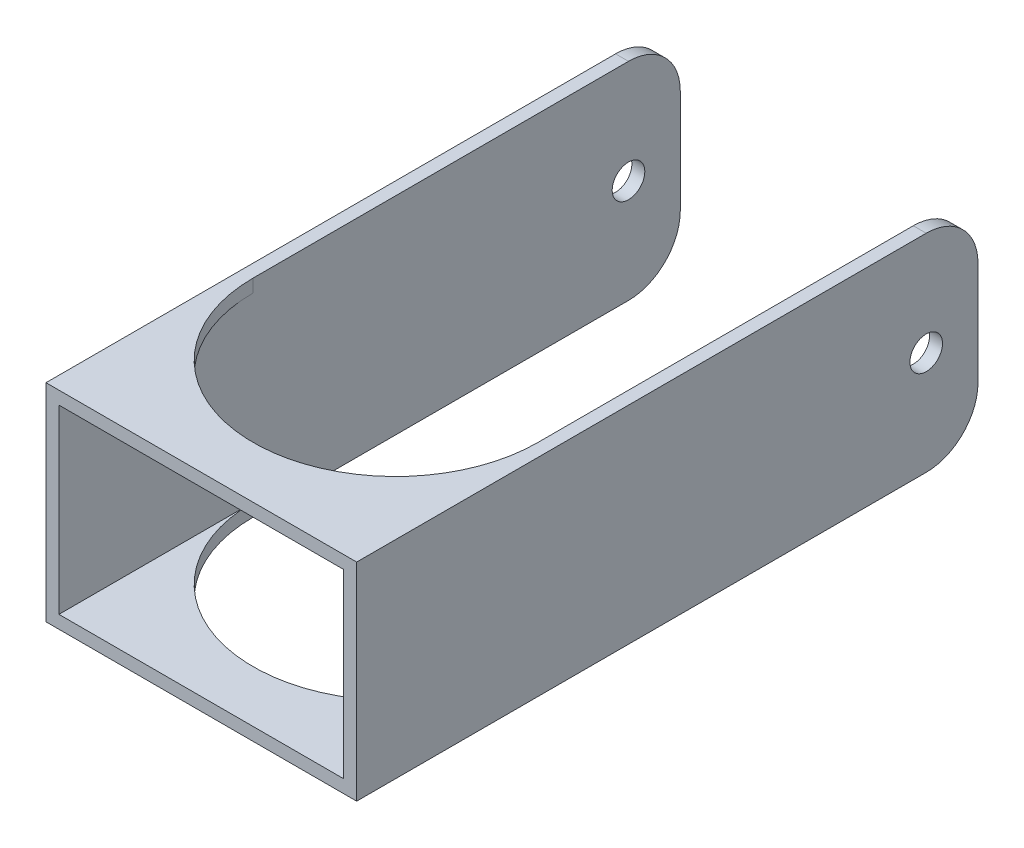
SolidWorks part; units mm, degrees
ref_plane "Front Plane" through (0, 0, 0) normal (0, 0, 1) x (1, 0, 0)
ref_plane "Top Plane" through (0, 0, 0) normal (0, 1, 0) x (1, 0, 0)
ref_plane "Right Plane" through (0, 0, 0) normal (1, 0, 0) x (0, 0, -1)
sketch "Sketch1" plane through (0, 0, 0) normal (0, 0, 1) x (1, 0, 0)
  line L0 (38.1, 0) -> (34.925, 0) construction
  line L1 (-38.1, 0) -> (38.1, 0) construction
  line L2 (0, 25.4) -> (0, -25.4)
  point P7 (0, 0)
sketch "Sketch2" plane through (0, 0, 0) normal (1, 0, 0) x (0, 0, -1)
  line L0 (76.2, 0) -> (-76.2, 0)
  point P4 (0, 0)
  dimension "Length" = 152.4
sketch "Sketch3" plane through (0, 0, 0) normal (0, 0, 1) x (1, 0, 0)
  line L0 (-38.1, 0) -> (38.1, 0) construction
  line L5 (38.1, -25.4) -> (-38.1, -25.4)
  line L6 (38.1, -25.4) -> (38.1, 25.4)
  line L11 (38.1, 25.4) -> (-38.1, 25.4)
  line L12 (-38.1, -25.4) -> (-38.1, 25.4)
  line L14 (38.1, -25.4) -> (-38.1, 25.4) construction
  line L15 (38.1, 25.4) -> (-38.1, -25.4) construction
  line L16 (34.925, -22.225) -> (-34.925, -22.225)
  line L17 (34.925, -22.225) -> (34.925, 22.225)
  line L18 (34.925, 22.225) -> (-34.925, 22.225)
  line L19 (-34.925, -22.225) -> (-34.925, 22.225)
  line L20 (34.925, -22.225) -> (-34.925, 22.225) construction
  line L21 (34.925, 22.225) -> (-34.925, -22.225) construction
  point P0 (0, 0)
  point P5 (0, 0)
  point P13 (34.925, -25.4)
  dimension "D1" = 3.175
  dimension "D3" = 76.2
  dimension "D4" = 50.8
  dimension "D2" = 3.175
extrude "Boss-Extrude1" add sketch "Sketch3" along normal up to vertex (76.2 mm away) and the other way up to vertex (76.2 mm away) up to point (0, 0, 76.2) other way up to point (0, 0, -76.2)
sketch "Sketch5" plane through (0, 0, 0) normal (1, 0, 0) x (0, 0, -1)
  line L0 (-76.2, 0) -> (76.2, 0) construction
  line L3 (-76.2, -25.4) -> (-76.2, 25.4) construction
  line L4 (76.2, -25.4) -> (76.2, 25.4) construction
  point P6 (9.525, 0)
  point P7 (38.1, 0)
  point P8 (-38.1, 0)
  point P10 (-9.525, 0)
  dimension "D1" = 85.725
  dimension "D2" = 114.3
  dimension "D3" = 85.725
  dimension "D4" = 114.3
sketch "Sketch6" plane through (0, 25.4, 0) normal (0, 1, 0) x (1, 0, 0)
  line L0 (-34.925, 76.2) -> (-34.925, -28.575)
  line L1 (38.1, 76.2) -> (-38.1, 76.2) construction
  line L2 (34.925, 76.2) -> (34.925, -28.575)
  line L3 (38.1, -76.2) -> (-38.1, -76.2) construction
  line L4 (-38.1, -76.2) -> (-38.1, 76.2) construction
  line L5 (38.1, -76.2) -> (38.1, 76.2) construction
  arc A0 (-34.925, -28.575) -> (34.925, -28.575) centre (0, -28.575) ccw
  line M4 (38.1, 76.2) -> (-38.1, 76.2)
  dimension "D1" = 12.7
  dimension "D2" = 3.175
  dimension "D3" = 3.175
extrude "Cut-Extrude1" cut sketch "Sketch6" against normal through all and the other way through all contours L0 A0 L2 M4
sketch "Sketch7" plane through (38.1, 0, 0) normal (1, 0, 0) x (0, 0, -1)
  line L2 (76.2, -25.4) -> (76.2, 25.4) construction
  circle A0 centre (63.5, 0) radius 4
  dimension "D1" = 8
  dimension "D2" = 12.7
extrude "Cut-Extrude2" cut sketch "Sketch7" against normal through all
fillet "Fillet1" radius 12.7 4 edges at (-36.5125, -25.4, -76.2) (-36.5125, 25.4, -76.2) (36.5125, -25.4, -76.2) (36.5125, 25.4, -76.2)
equation "\"D1@Sketch3\"=\"Wall thickness@Sketch1\""
equation "\"D1@Sketch5\"=\"Width@Sketch1\"*1.125"
equation "\"D2@Sketch5\"=\"Width@Sketch1\"*1.5"
equation "\"D3@Sketch5\"=\"D1@Sketch5\""
equation "\"D4@Sketch5\"=\"D2@Sketch5\""
equation "\"D2@Sketch3\"=\"Wall Thickness@Sketch1\""
